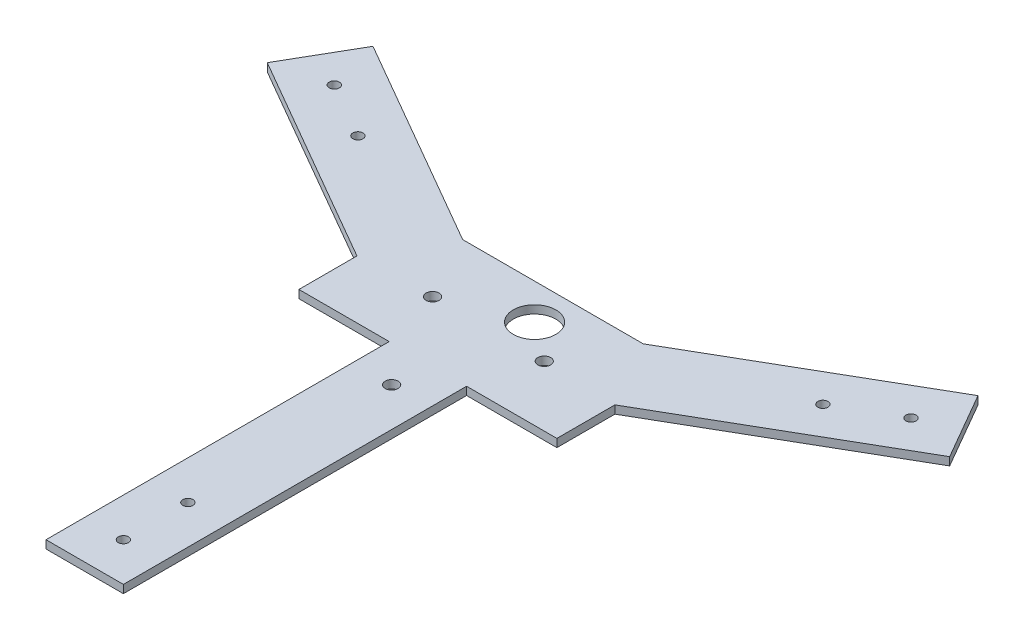
SolidWorks part; units mm, degrees
ref_plane "Front Plane" through (0, 0, 0) normal (0, 0, 1) x (1, 0, 0)
ref_plane "Top Plane" through (0, 0, 0) normal (0, 1, 0) x (1, 0, 0)
ref_plane "Right Plane" through (0, 0, 0) normal (1, 0, 0) x (0, 0, -1)
sketch "Sketch1" plane through (0, 0, 0) normal (0, 1, 0) x (1, 0, 0)
  line L0 (0, 11.43) -> (7.62, 24.6282)
  line L1 (0, 0) -> (50.8, 0)
  line L2 (0, 0) -> (0, 11.43)
  line L3 (0, 11.43) -> (50.8, 11.43)
  line L4 (50.8, 0) -> (50.8, 11.43)
  line L5 (50.8, 11.43) -> (43.18, 24.6282)
  line L6 (7.62, 24.6282) -> (43.18, 24.6282)
  line L7 (3.81, 18.0291) -> (44.3832, -5.3958) construction
  line L8 (17.78, 0) -> (33.02, 0)
  line L9 (17.78, 0) -> (17.78, -19.3279)
  line L10 (17.78, -19.3279) -> (33.02, -19.3279)
  line L11 (33.02, 0) -> (33.02, -19.3279)
  line L12 (46.99, 18.0291) -> (8.5613, -4.1577) construction
  line L13 (25.4, -19.3279) -> (25.4, 20.0669) construction
  line L14 (17.78, -19.3279) -> (33.02, -19.3279)
  line L15 (17.78, -19.3279) -> (17.78, -67.5879)
  line L16 (33.02, -19.3279) -> (33.02, -67.5879)
  line L17 (17.78, -67.5879) -> (33.02, -67.5879)
  line L18 (0, 11.43) -> (7.62, 24.6282)
  line L19 (0, 11.43) -> (-41.7944, 35.56)
  line L20 (7.62, 24.6282) -> (-34.1744, 48.7582)
  line L21 (-41.7944, 35.56) -> (-34.1744, 48.7582)
  line L22 (50.8, 11.43) -> (43.18, 24.6282)
  line L23 (50.8, 11.43) -> (92.5944, 35.56)
  line L24 (43.18, 24.6282) -> (84.9744, 48.7582)
  line L25 (92.5944, 35.56) -> (84.9744, 48.7582)
  circle A2 centre (36.3985, 11.9141) radius 1.27
  circle A5 centre (14.4015, 11.9141) radius 1.27
  circle A8 centre (25.4, -7.1359) radius 1.27
  point P23 (25.4, 5.5641)
  dimension "D11" = 48.26
  dimension "D12" = 48.26
  dimension "D13" = 2.54
  dimension "D14" = 48.26
  dimension "D16" = 12.7
  dimension "D21" = 2.54
  dimension "D24" = 12.7
  dimension "D26" = 2.54
  dimension "D1" = 50.8
  dimension "D2" = 11.43
  dimension "D3" = 30
  dimension "D4" = 15.24
  dimension "D5" = 30
  dimension "D6" = 15.24
  dimension "D7" = 15.24
  dimension "D8" = 24.892
  dimension "D9" = 17.78
  dimension "D10" = 12.7
extrude "Boss-Extrude2" add sketch "Sketch1" along normal blind 1.5875
sketch "Sketch3" plane through (0, 1.5875, 0) normal (0, 1, 0) x (1, 0, 0)
  line L0 (7.62, 24.6282) -> (43.18, 24.6282) construction
  circle A0 centre (28.7785, 17.628) radius 4.191
  circle A1 centre (36.3985, 11.9141) radius 1.27 construction
  dimension "D1" = 8.382
  dimension "D2" = 7.0002
  dimension "D3" = 7.62
extrude "Cut-Extrude1" cut sketch "Sketch3" against normal blind 2.54
sketch "Sketch4" plane through (0, 1.5875, 0) normal (0, 1, 0) x (1, 0, 0)
  line L0 (17.78, 0) -> (17.78, -67.5879) construction
  line L1 (17.78, -67.5879) -> (33.02, -67.5879) construction
  line L2 (-41.7944, 35.56) -> (-34.1744, 48.7582) construction
  line L3 (0, 11.43) -> (-41.7944, 35.56) construction
  line L4 (43.18, 24.6282) -> (84.9744, 48.7582) construction
  line L5 (92.5944, 35.56) -> (84.9744, 48.7582) construction
  circle A0 centre (25.4, -59.9679) radius 1
  circle A1 centre (25.4, -47.2679) radius 1
  circle A2 centre (-20.3867, 31.9991) radius 1
  circle A3 centre (-31.3853, 38.3491) radius 1
  circle A4 centre (82.1853, 38.3491) radius 1
  circle A5 centre (71.1867, 31.9991) radius 1
  dimension "D1" = 2
  dimension "D2" = 2
  dimension "D3" = 7.62
  dimension "D4" = 7.62
  dimension "D5" = 7.62
  dimension "D6" = 20.32
  dimension "D7" = 7.62
  dimension "D8" = 20.32
  dimension "D9" = 7.62
  dimension "D10" = 7.62
  dimension "D11" = 2
  dimension "D12" = 2
  dimension "D13" = 7.62
  dimension "D14" = 7.62
  dimension "D15" = 7.62
  dimension "D16" = 20.32
  dimension "D17" = 2
  dimension "D18" = 2
extrude "Cut-Extrude2" cut sketch "Sketch4" against normal blind 2.54
